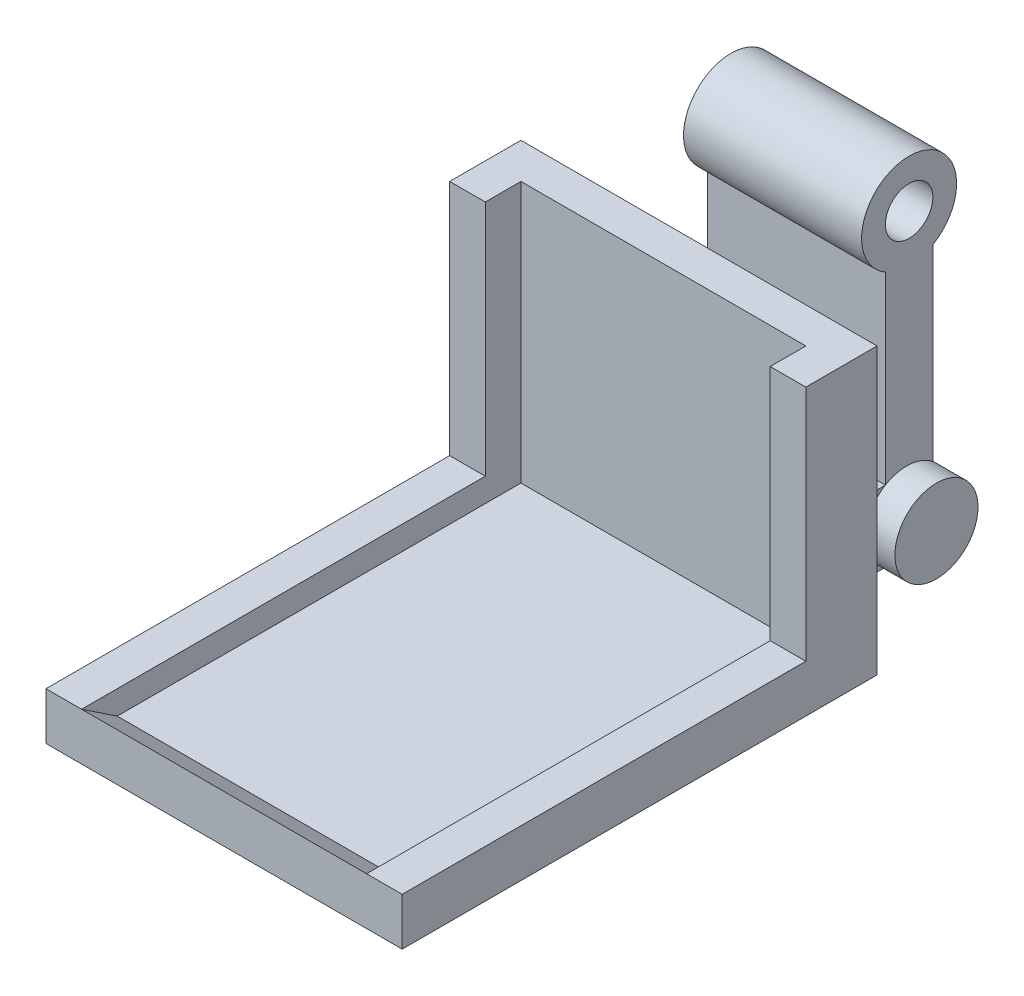
SolidWorks part; units mm, degrees
ref_plane "Front Plane" through (0, 0, 0) normal (0, 0, 1) x (1, 0, 0)
ref_plane "Top Plane" through (0, 0, 0) normal (0, 1, 0) x (1, 0, 0)
ref_plane "Right Plane" through (0, 0, 0) normal (1, 0, 0) x (0, 0, -1)
sketch "Sketch2" plane through (0, 0, 0) normal (1, 0, 0) x (0, 0, -1)
  circle A0 centre (0, 0) radius 1.75
extrude "Boss-Extrude1" add sketch "Sketch2" along normal blind 10
sketch "Sketch3" plane through (0, 0, 0) normal (0, 0, 1) x (1, 0, 0)
  line L0 (0, -1.925) -> (0, 1.925) construction
  line L1 (1.25, 1.5) -> (8.75, 1.5)
  line L2 (1.25, 1.5) -> (1.25, -1.5)
  line L3 (1.25, -1.5) -> (8.75, -1.5)
  line L4 (8.75, 1.5) -> (8.75, -1.5)
  line L5 (10, 1.75) -> (0, 1.75) construction
  point P4 (5, -1.5)
  point P7 (1.25, 0)
  dimension "D1" = 7.5
  dimension "D2" = 5
  dimension "D3" = 1.75
  dimension "D4" = 3
extrude "Boss-Extrude2" add sketch "Sketch3" along normal blind 5
sketch "Sketch4" plane through (0, 0, 5) normal (0, 0, 1) x (1, 0, 0)
  line L0 (8.75, 1.5) -> (1.25, 1.5) construction
  line L1 (-2.5, 0.5) -> (12.5, 0.5)
  line L2 (-2.5, 0.5) -> (-2.5, -1.5)
  line L3 (-2.5, -1.5) -> (12.5, -1.5)
  line L4 (12.5, 0.5) -> (12.5, -1.5)
  point P4 (5, 0.5)
  point P7 (5, 1.5)
  point P8 (-2.5, -0.5)
  dimension "D1" = 15
  dimension "D2" = 0
  dimension "D3" = 2
  dimension "D4" = 1
extrude "Boss-Extrude3" add sketch "Sketch4" along normal blind 20
sketch "Sketch5" plane through (0, 0.5, 0) normal (0, 1, 0) x (1, 0, 0)
  line L0 (8.75, -5) -> (1.25, -5) construction
  line L1 (-1, -6.5) -> (11, -6.5)
  line L2 (-1, -6.5) -> (-1, -23.5)
  line L3 (-1, -23.5) -> (11, -23.5)
  line L4 (11, -6.5) -> (11, -23.5)
  line L5 (-2.5, -25) -> (-2.5, -5) construction
  line L6 (12.5, -25) -> (12.5, -5) construction
  line L7 (12.5, -25) -> (-2.5, -25) construction
  dimension "D1" = 1.5
  dimension "D2" = 1.5
  dimension "D3" = 1.5
  dimension "D4" = 1.5
extrude "Cut-Extrude1" cut sketch "Sketch5" against normal blind 1
sketch "Sketch6" plane through (11, 0, 0) normal (-1, 0, 0) x (0, 0, 1)
  line L0 (23.5, -0.5) -> (25, 0.5)
  line L1 (25, 0.5) -> (23.5, 0.5)
  line L2 (23.5, 0.5) -> (23.5, -0.5)
  dimension "D1" = 1.5
  dimension "D2" = 90
extrude "Cut-Extrude2" cut sketch "Sketch6" along normal blind 12
sketch "Sketch7" plane through (0, 0.5, 0) normal (0, 1, 0) x (1, 0, 0)
  line L0 (-2.5, -5) -> (12.5, -5)
  line L1 (12.5, -5) -> (12.5, -8)
  line L2 (12.5, -25) -> (12.5, -5) construction
  line L3 (12.5, -8) -> (11, -8)
  line L4 (11, -25) -> (11, -6.5) construction
  line L5 (11, -8) -> (11, -6.5)
  line L6 (11, -6.5) -> (-1, -6.5)
  line L7 (-1, -6.5) -> (-1, -8)
  line L8 (-1, -6.5) -> (-1, -23.5) construction
  line L9 (-1, -8) -> (-2.5, -8)
  line L10 (-2.5, -25) -> (-2.5, -5) construction
  line L11 (-2.5, -8) -> (-2.5, -5)
  dimension "D1" = 3
  dimension "D2" = 3
extrude "Boss-Extrude4" add sketch "Sketch7" along normal blind 10
sketch "Sketch8" plane through (0, 0, 0) normal (0, 1, 0) x (1, 0, 0)
  line L1 (1.25, -0.9014) -> (8.75, -0.9014)
  line L2 (1.25, -0.9014) -> (1.25, 1.0986)
  line L3 (1.25, 1.0986) -> (8.75, 1.0986)
  line L4 (8.75, -0.9014) -> (8.75, 1.0986)
  dimension "D1" = 2
  dimension "D2" = 7.5
extrude "Boss-Extrude5" add sketch "Sketch8" along normal blind 11
sketch "Sketch9" plane through (1.25, 0, 0) normal (-1, 0, 0) x (0, 0, 1)
  line L0 (-1.0986, 11) -> (0.9014, 11) construction
  line L1 (0.9014, 11) -> (0.9014, 1.5) construction
  circle A0 centre (-0.0986, 11) radius 2
  point P4 (0, 0)
  dimension "D1" = 0
  dimension "D2" = 4
  dimension "D3" = 1
extrude "Boss-Extrude6" add sketch "Sketch9" against normal up to vertex
sketch "Sketch10" plane through (1.25, 0, 0) normal (-1, 0, 0) x (0, 0, 1)
  circle A0 centre (-0.0986, 11) radius 1
extrude "Cut-Extrude3" cut sketch "Sketch10" against normal through all
